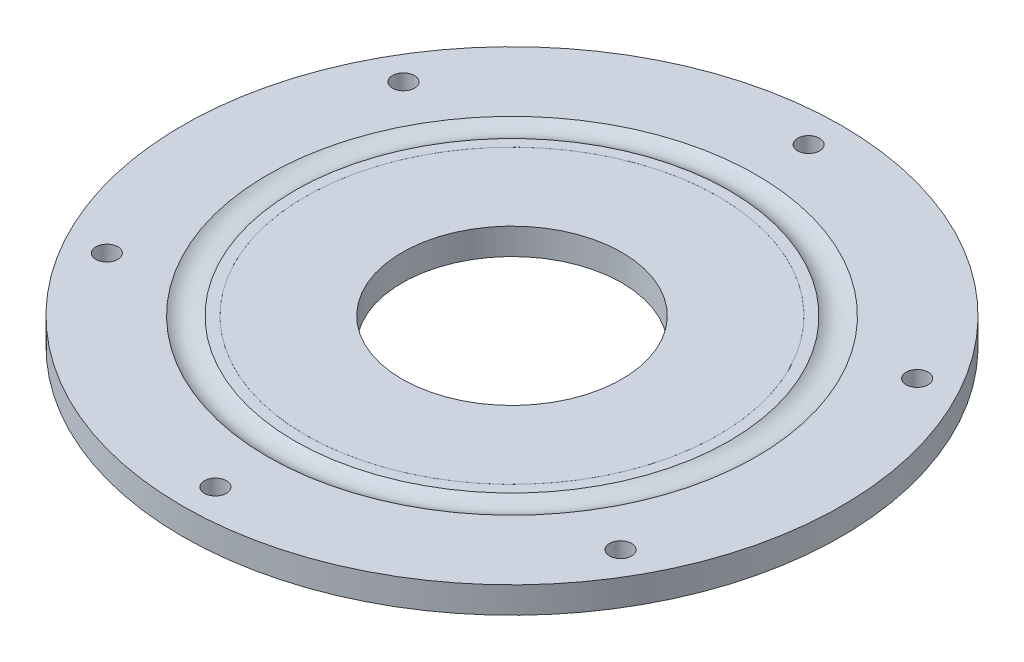
SolidWorks part; units mm, degrees
ref_plane "Front Plane" through (0, 0, 0) normal (0, 0, 1) x (1, 0, 0)
ref_plane "Top Plane" through (0, 0, 0) normal (0, 1, 0) x (1, 0, 0)
ref_plane "Right Plane" through (0, 0, 0) normal (1, 0, 0) x (0, 0, -1)
ref_plane "Plane1" through (0, 0, 0) normal (0, 0, -1) x (-1, 0, 0)
sketch "Sketch1" plane through (0, 0, 0) normal (0, 0, -1) x (-1, 0, 0)
  line L0 (-59, 0.8724) -> (-47, 0.8724)
  line L1 (-46, 1.8724) -> (-46, 5.8724)
  line L2 (-46, 5.8724) -> (-47, 6.8724)
  line L3 (-47, 6.8724) -> (-49.4043, 6.8724)
  line L4 (-55.5957, 6.8724) -> (-59, 6.8724)
  line L5 (-59, 6.8724) -> (-60, 5.8724)
  line L6 (-60, 5.8724) -> (-60, 1.8724)
  line L7 (0, 0) -> (0, 6.8724) construction
  arc A0 (-47, 0.8724) -> (-46, 1.8724) centre (-47, 1.8724) ccw
  arc A1 (-49.4043, 6.8724) -> (-55.5957, 6.8724) centre (-52.5, 11) cw
  arc A2 (-60, 1.8724) -> (-59, 0.8724) centre (-59, 1.8724) ccw
  dimension "D1" = 5.1595
  dimension "D2" = 14
  dimension "D3" = 6.1914
  dimension "D4" = 6
revolve "Revolve1" add sketch "Sketch1" angle 360 about L7
sketch "Sketch2" plane through (0, 0.8724, 0) normal (0, -1, 0) x (1, 0, 0)
  circle A0 centre (0, 0) radius 75
  circle A2 centre (0, 0) radius 46.9929
  circle A3 centre (0, 0) radius 59
  dimension "D1" = 150
extrude "Boss-Extrude1" add sketch "Sketch2" against normal blind 6 contours A0 A3 | A2
sketch "Sketch7" plane through (0, 0.8724, 0) normal (0, -1, 0) x (1, 0, 0)
  circle A1 centre (0, 0) radius 15
extrude "Cut-Extrude3" [suppressed] cut sketch "Sketch7" against normal blind 3
sketch "Sketch8" plane through (0, 6.8724, 0) normal (0, 1, 0) x (1, 0, 0)
  circle A0 centre (0, 0) radius 25
  dimension "D1" = 50
extrude "Cut-Extrude4" cut sketch "Sketch8" against normal blind 6
sketch "Sketch9" plane through (0, 0.8724, 0) normal (0, -1, 0) x (1, 0, 0)
  circle A0 centre (0, 0) radius 67.5 construction
  circle A1 centre (0, 67.5) radius 2.5
  circle A2 centre (58.4567, 33.75) radius 2.5
  circle A3 centre (58.4567, -33.75) radius 2.5
  circle A4 centre (0, -67.5) radius 2.5
  circle A5 centre (-58.4567, -33.75) radius 2.5
  circle A6 centre (-58.4567, 33.75) radius 2.5
  point P21 (0, 0)
  dimension "D1" = 135
  dimension "D2" = 6
extrude "Cut-Extrude5" cut sketch "Sketch9" against normal blind 10
